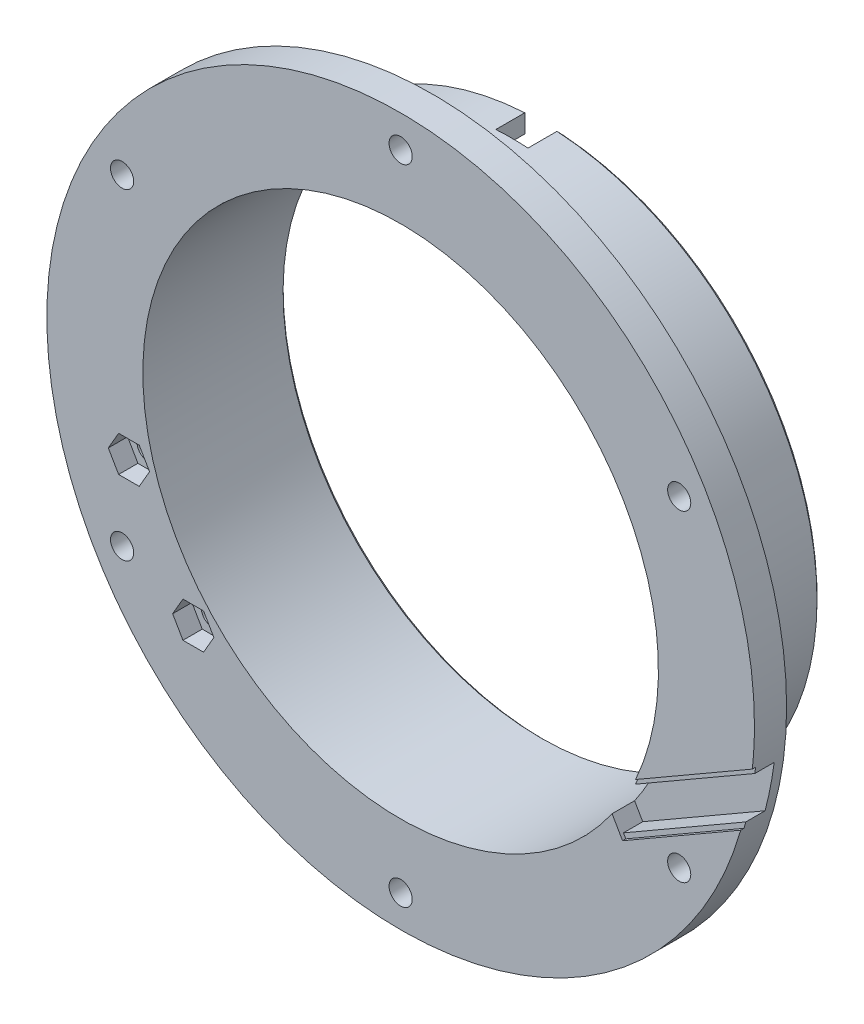
SolidWorks part; units mm, degrees
ref_plane "Front Plane" through (0, 0, 0) normal (0, 0, 1) x (1, 0, 0)
ref_plane "Top Plane" through (0, 0, 0) normal (0, 1, 0) x (1, 0, 0)
ref_plane "Right Plane" through (0, 0, 0) normal (1, 0, 0) x (0, 0, -1)
sketch "Sketch1" plane through (0, 0, 0) normal (0, 1, 0) x (1, 0, 0)
  line L0 (0, -94.2188) -> (0, 47.6563) construction
  line L1 (-85, 0) -> (81.25, 0) construction
  line L2 (35, 0) -> (35, -22.3)
  line L3 (35, -22.3) -> (55, -22.3)
  line L4 (55, -22.3) -> (55, -17.3)
  line L5 (55, -17.3) -> (49, -17.3)
  line L6 (49, -17.3) -> (49, 0)
  line L7 (49, 0) -> (35, 0)
  dimension "D1" = 5
  dimension "D2" = 17.3
  dimension "D3" = 55
  dimension "D4" = 35
  dimension "D5" = 6
revolve "Revolve1" add sketch "Sketch1" angle 360 about L0
sketch "Sketch2" plane through (0, 0, 22.3) normal (0, 0, 1) x (1, 0, 0)
  line L0 (0, 92.3026) -> (0, -73.5883) construction
  circle A0 centre (0, 50) radius 1.8
  circle A1 centre (43.3013, 25) radius 1.8
  circle A2 centre (43.3013, -25) radius 1.8
  circle A3 centre (0, -50) radius 1.8
  circle A4 centre (-43.3013, -25) radius 1.8
  circle A5 centre (-43.3013, 25) radius 1.8
  point P17 (0, 0)
  dimension "D1" = 3.6
  dimension "D2" = 50
  dimension "D3" = 6
extrude "Cut-Extrude1" cut sketch "Sketch2" against normal blind 11
sketch "Sketch3" plane through (0, 0, 0) normal (0, 0, 1) x (1, 0, 0)
  line L0 (0, 68.2701) -> (0, -64.8183) construction
  line L1 (72.5343, 0) -> (-87.8133, 0) construction
  line L2 (2.5, 48.9362) -> (2.5, 34.9106)
  line L3 (-2.5, 48.9362) -> (-2.5, 34.9106)
  arc A0 (2.5, 34.9106) -> (-2.5, 34.9106) centre (0, 0) ccw
  circle A2 centre (0, 0) radius 49 construction
  arc A3 (2.5, 48.9362) -> (-2.5, 48.9362) centre (0, 0) ccw
  dimension "D1" = 70
  dimension "D2" = 2.5
extrude "Cut-Extrude2" cut sketch "Sketch3" along normal blind 5
sketch "Sketch4" plane through (0, 0, 0) normal (0, 0, -1) x (-1, 0, 0)
  circle A0 centre (0, 0) radius 42.925
  dimension "D1" = 85.85
extrude "Cut-Extrude3" cut sketch "Sketch4" against normal up to surface (17.3 mm away) flip side to cut up to face at (0, 0, 17.3)
sketch "Sketch6" plane through (0, 0, 0) normal (0, 0, 1) x (1, 0, 0)
  circle A0 centre (0, 0) radius 40.075
  dimension "D1" = 80.15
extrude "Cut-Extrude5" cut sketch "Sketch6" along normal through all
chamfer "Chamfer1" distance 0.5 angle 45 4 edges at (-2.5, 41.4245, 0) (0, -40.075, 0) (2.5, 41.4245, 0) (0, -42.925, 0)
sketch "Sketch7" plane through (0, 0, 22.3) normal (0, 0, 1) x (1, 0, 0)
  line L0 (0, 58.6347) -> (0, -59.6699) construction
  line L1 (-69.2507, 0) -> (77.1724, 0) construction
  line L2 (0, 0) -> (68.0196, 39.2712) construction
  line L3 (0, 0) -> (38.383, -66.4813) construction
  line L4 (14.5962, 28.7187) -> (69.5582, -66.4784) construction
  line L5 (10.4252, -35.6079) -> (83.1891, 6.4023) construction
  line L6 (31.3599, -20.317) -> (34.1349, -25.1234)
  line L7 (31.3599, -20.317) -> (55.6086, -6.317)
  line L8 (55.6086, -6.317) -> (58.3836, -11.1234)
  line L9 (58.3836, -11.1234) -> (34.1349, -25.1234)
  dimension "D1" = 30
  dimension "D2" = 90
  dimension "D3" = 27
  dimension "D4" = 36.05
  dimension "D5" = 5.55
  dimension "D6" = 2.775
  dimension "D7" = 10
  dimension "D8" = 28
extrude "Cut-Extrude6" cut sketch "Sketch7" against normal blind 3.5
sketch "Sketch8" plane through (0, 0, 22.3) normal (0, 0, 1) x (1, 0, 0)
  line L0 (0, 0) -> (-43.3013, -25) construction
  line L1 (0, 0) -> (32.0331, -55.483) construction
  line L2 (-47.4412, -3.8294) -> (-27.4108, -38.523) construction
  line L3 (-29.0348, -30.1603) -> (-30.6369, -32.9353)
  line L4 (-43.8412, -10.0647) -> (-45.4434, -12.8397)
  line L5 (-45.4434, -12.8397) -> (-43.8412, -15.6147)
  line L6 (-43.8412, -15.6147) -> (-40.6369, -15.6147)
  line L7 (-40.6369, -15.6147) -> (-39.0348, -12.8397)
  line L8 (-39.0348, -12.8397) -> (-40.6369, -10.0647)
  line L9 (-40.6369, -10.0647) -> (-43.8412, -10.0647)
  line L10 (-30.6369, -27.3853) -> (-29.0348, -30.1603)
  line L11 (-33.8412, -27.3853) -> (-30.6369, -27.3853)
  line L12 (-35.4434, -30.1603) -> (-33.8412, -27.3853)
  line L13 (-33.8412, -32.9353) -> (-35.4434, -30.1603)
  line L14 (-30.6369, -32.9353) -> (-33.8412, -32.9353)
  circle A0 centre (-42.2391, -12.8397) radius 2.775 construction
  dimension "D2" = 5.55
  dimension "D3" = 10
  dimension "D1" = 43
extrude "Cut-Extrude7" cut sketch "Sketch8" against normal blind 3
sketch "Sketch9" plane through (0, 0, 22.3) normal (0, 0, 1) x (1, 0, 0)
  line L0 (0, 0) -> (-43.3013, -25) construction
  circle A0 centre (-42.2391, -12.8397) radius 1.75
  circle A1 centre (-32.2391, -30.1603) radius 1.75
  dimension "D1" = 3.5
extrude "Cut-Extrude9" cut sketch "Sketch9" against normal blind 5
sketch "Sketch10" plane through (0, 0, 22.3) normal (0, 0, 1) x (1, 0, 0)
  line L0 (10.4252, -35.6079) -> (78.987, 3.9762) construction
  line L1 (10.4252, -35.6079) -> (83.1891, 6.4023) construction
  line L2 (30.9974, -19.6891) -> (34.4974, -25.7513)
  line L3 (31.3599, -20.317) -> (34.1349, -25.1234) construction
  line L4 (34.4974, -25.7513) -> (59.1621, -11.5112)
  line L5 (59.1621, -11.5112) -> (55.6621, -5.449)
  line L6 (55.6621, -5.449) -> (30.9974, -19.6891)
  dimension "D1" = 7
  dimension "D2" = 3.5
extrude "Cut-Extrude10" cut sketch "Sketch10" against normal blind 0.5
